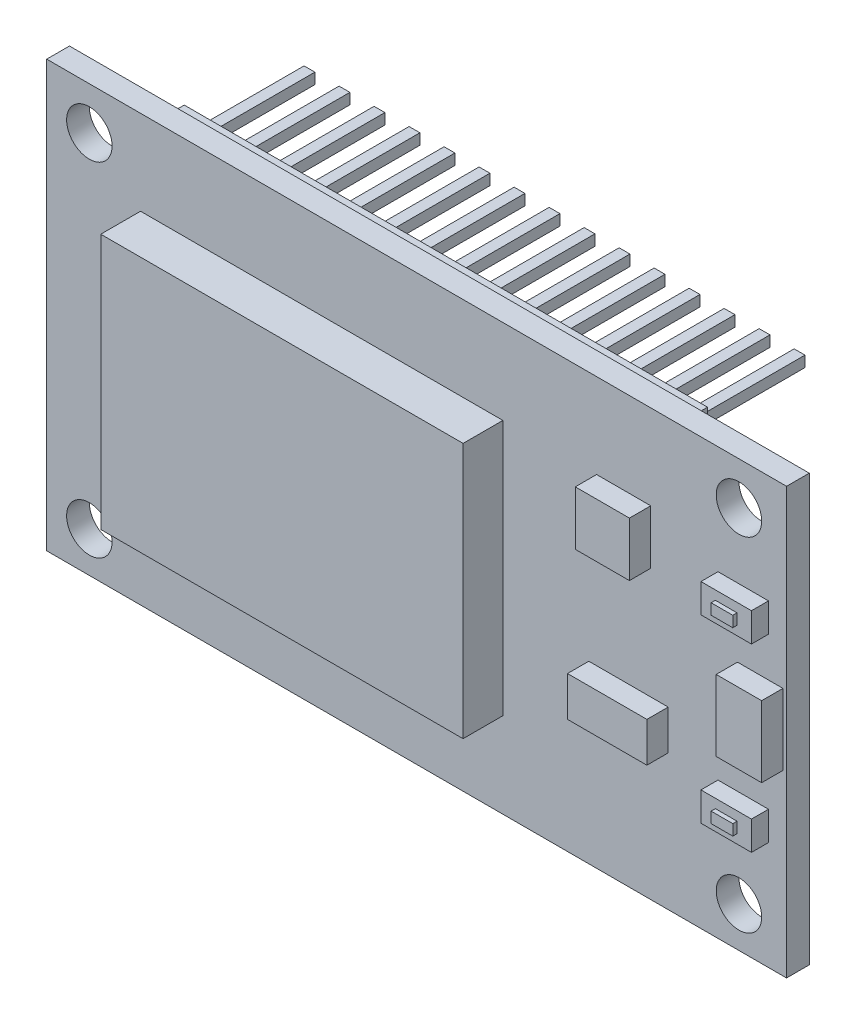
SolidWorks part; units mm, degrees
ref_plane "Front Plane" through (0, 0, 0) normal (0, 0, 1) x (1, 0, 0)
ref_plane "Top Plane" through (0, 0, 0) normal (0, 1, 0) x (1, 0, 0)
ref_plane "Right Plane" through (0, 0, 0) normal (1, 0, 0) x (0, 0, -1)
sketch "Sketch1" plane through (0, 0, 0) normal (0, 0, 1) x (1, 0, 0)
  line L1 (0, 0) -> (52.07, 0)
  line L2 (0, 0) -> (0, 29.972)
  line L3 (0, 29.972) -> (52.07, 29.972)
  line L4 (52.07, 0) -> (52.07, 29.972)
  dimension "D1" = 52.07
  dimension "D2" = 29.972
extrude "Boss-Extrude1" add sketch "Sketch1" along normal blind 1.6
sketch "Sketch2" plane through (0, 0, 0) normal (0, 0, 1) x (1, 0, 0)
  line L0 (52.07, 29.972) -> (0, 29.972) construction
  line L1 (0, 29.972) -> (0, 0) construction
  circle A0 centre (3, 26.972) radius 1.6
  dimension "D1" = 3.2
  dimension "D2" = 3
  dimension "D3" = 3
extrude "Cut-Extrude1" cut sketch "Sketch2" along normal blind 1.6
pattern_linear "LPattern1" count 2 spacing 45.72 along (1, 0, 0) of "Cut-Extrude1"
pattern_linear "LPattern2" count 2 spacing 24.13 along (0, -1, 0) of "Cut-Extrude1", "LPattern1"
sketch "Sketch3" plane through (0, 0, 0) normal (0, 0, -1) x (-1, 0, 0)
  line L1 (-42.878, 28.3807) -> (-6.048, 28.3807)
  line L2 (-42.878, 28.3807) -> (-42.878, 25.5867)
  line L3 (-42.878, 25.5867) -> (-6.048, 25.5867)
  line L4 (-6.048, 28.3807) -> (-6.048, 25.5867)
  circle A0 centre (-3, 26.972) radius 1.6 construction
  dimension "D1" = 36.83
  dimension "D2" = 2.794
  dimension "D3" = 3.048
extrude "Boss-Extrude2" add sketch "Sketch3" along normal blind 2.032
sketch "Sketch4" plane through (0, 0, -2.032) normal (0, 0, -1) x (-1, 0, 0)
  line L0 (-6.048, 28.3807) -> (-42.878, 28.3807) construction
  line L1 (-42.116, 27.3647) -> (-41.354, 27.3647)
  line L2 (-42.116, 27.3647) -> (-42.116, 26.6027)
  line L3 (-42.116, 26.6027) -> (-41.354, 26.6027)
  line L4 (-41.354, 27.3647) -> (-41.354, 26.6027)
  line L6 (-42.878, 28.3807) -> (-42.878, 25.5867) construction
  dimension "D1" = 0.762
  dimension "D2" = 0.762
  dimension "D3" = 1.016
  dimension "D4" = 0.762
extrude "Boss-Extrude3" add sketch "Sketch4" along normal blind 7.62
pattern_linear "LPattern3" count 15 spacing 2.4638 along (-1, 0, 0) of "Boss-Extrude3"
pattern_linear "LPattern4" count 2 spacing 24.13 along (0, -1, 0) of "Boss-Extrude3", "Boss-Extrude2", "LPattern3"
sketch "Sketch5" plane through (0, 0, 1.6) normal (0, 0, 1) x (1, 0, 0)
  line L0 (0, 29.972) -> (0, 0) construction
  line L1 (6.604, 24.003) -> (32.104, 24.003)
  line L2 (6.604, 24.003) -> (6.604, 6.003)
  line L3 (6.604, 6.003) -> (32.104, 6.003)
  line L4 (32.104, 24.003) -> (32.104, 6.003)
  line L5 (52.07, 29.972) -> (0, 29.972) construction
  dimension "D1" = 25.5
  dimension "D2" = 18
  dimension "D3" = 6.604
  dimension "D4" = 5.969
extrude "Boss-Extrude4" add sketch "Sketch5" along normal blind 2.8
sketch "Sketch7" plane through (0, 0, 1.6) normal (0, 0, 1) x (1, 0, 0)
  line L0 (52.07, 0) -> (52.07, 29.972) construction
  line L1 (48.616, 17.526) -> (51.816, 17.526)
  line L2 (48.616, 17.526) -> (48.616, 12.526)
  line L3 (48.616, 12.526) -> (51.816, 12.526)
  line L4 (51.816, 17.526) -> (51.816, 12.526)
  line L5 (52.07, 29.972) -> (0, 29.972) construction
  dimension "D1" = 3.2
  dimension "D2" = 5
  dimension "D3" = 0.254
  dimension "D4" = 12.446
extrude "Boss-Extrude5" add sketch "Sketch7" along normal blind 1.5
sketch "Sketch8" plane through (0, 0, 1.6) normal (0, 0, 1) x (1, 0, 0)
  line L0 (52.07, 29.972) -> (0, 29.972) construction
  line L1 (47.244, 22.352) -> (50.8, 22.352)
  line L2 (47.244, 22.352) -> (47.244, 20.32)
  line L3 (47.244, 20.32) -> (50.8, 20.32)
  line L4 (50.8, 22.352) -> (50.8, 20.32)
  line L5 (52.07, 0) -> (52.07, 29.972) construction
  dimension "D1" = 3.556
  dimension "D2" = 2.032
  dimension "D3" = 7.62
  dimension "D4" = 1.27
extrude "Boss-Extrude6" add sketch "Sketch8" along normal blind 1.2
sketch "Sketch9" plane through (0, 0, 2.8) normal (0, 0, 1) x (1, 0, 0)
  line L0 (50.8, 22.352) -> (47.244, 22.352) construction
  line L1 (48.26, 21.717) -> (49.784, 21.717)
  line L2 (48.26, 21.717) -> (48.26, 20.955)
  line L3 (48.26, 20.955) -> (49.784, 20.955)
  line L4 (49.784, 21.717) -> (49.784, 20.955)
  line L6 (50.8, 20.32) -> (50.8, 22.352) construction
  dimension "D1" = 1.524
  dimension "D2" = 0.762
  dimension "D3" = 0.635
  dimension "D4" = 1.016
extrude "Boss-Extrude7" add sketch "Sketch9" along normal blind 0.3
pattern_linear "LPattern5" count 2 spacing 12.7 along (0, -1, 0) of "Boss-Extrude7", "Boss-Extrude6"
sketch "Sketch10" plane through (0, 0, 1.6) normal (0, 0, 1) x (1, 0, 0)
  line L0 (32.104, 24.003) -> (52.07, 24.003) construction
  line L1 (52.07, 0) -> (52.07, 29.972) construction
  line L3 (38.7011, 24.003) -> (42.5111, 24.003)
  line L4 (38.7011, 24.003) -> (38.7011, 20.193)
  line L5 (38.7011, 20.193) -> (42.5111, 20.193)
  line L6 (42.5111, 24.003) -> (42.5111, 20.193)
  dimension "D1" = 3.81
  dimension "D2" = 3.81
extrude "Boss-Extrude8" add sketch "Sketch10" along normal blind 1.5
sketch "Sketch11" plane through (0, 0, 1.6) normal (0, 0, 1) x (1, 0, 0)
  line L1 (38.1527, 12.3495) -> (43.7407, 12.3495)
  line L2 (38.1527, 12.3495) -> (38.1527, 9.5555)
  line L3 (38.1527, 9.5555) -> (43.7407, 9.5555)
  line L4 (43.7407, 12.3495) -> (43.7407, 9.5555)
  dimension "D1" = 5.588
  dimension "D2" = 2.794
extrude "Boss-Extrude9" add sketch "Sketch11" along normal blind 1.5
